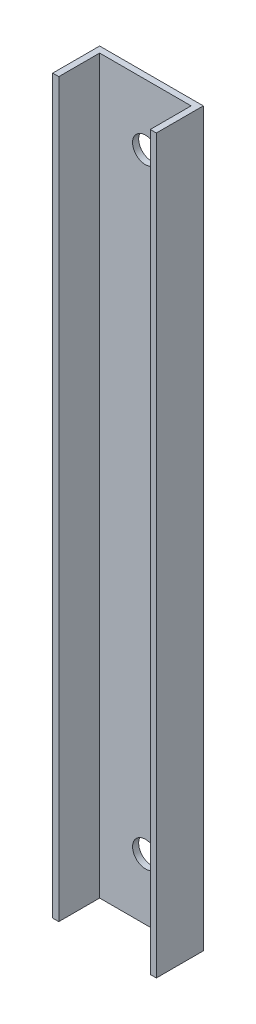
SolidWorks part; units mm, degrees
ref_plane "Front Plane" through (0, 0, 0) normal (0, 0, 1) x (1, 0, 0)
ref_plane "Top Plane" through (0, 0, 0) normal (0, 1, 0) x (1, 0, 0)
ref_plane "Right Plane" through (0, 0, 0) normal (1, 0, 0) x (0, 0, -1)
sketch "Sketch1" plane through (0, 0, 0) normal (0, 1, 0) x (1, 0, 0)
  line L0 (-10.9455, 0) -> (-10.9455, 7.7)
  line L1 (-10.9455, 7.7) -> (6.0545, 7.7)
  line L2 (6.0545, 7.7) -> (6.0545, 0)
  dimension "D1" = 7.7
  dimension "D2" = 17
extrude "Extrude-Thin1" add sketch "Sketch1" along normal blind 120 thin
sketch "Sketch2" plane through (0, 0, -6.7) normal (0, 0, 1) x (1, 0, 0)
  line L0 (-9.9455, 120) -> (5.0545, 120) construction
  line L1 (-10.9455, 120) -> (-10.9455, 0) construction
  line L2 (44.0821, 60) -> (-30.222, 60) construction
  circle A0 centre (-2.4455, 110) radius 2.1
  circle A1 centre (-2.4455, 10) radius 2.1
  dimension "D2" = 8.5
  dimension "D3" = 4.2
  dimension "D1" = 10
  dimension "D4" = 60
extrude "Cut-Extrude1" cut sketch "Sketch2" against normal blind 10
